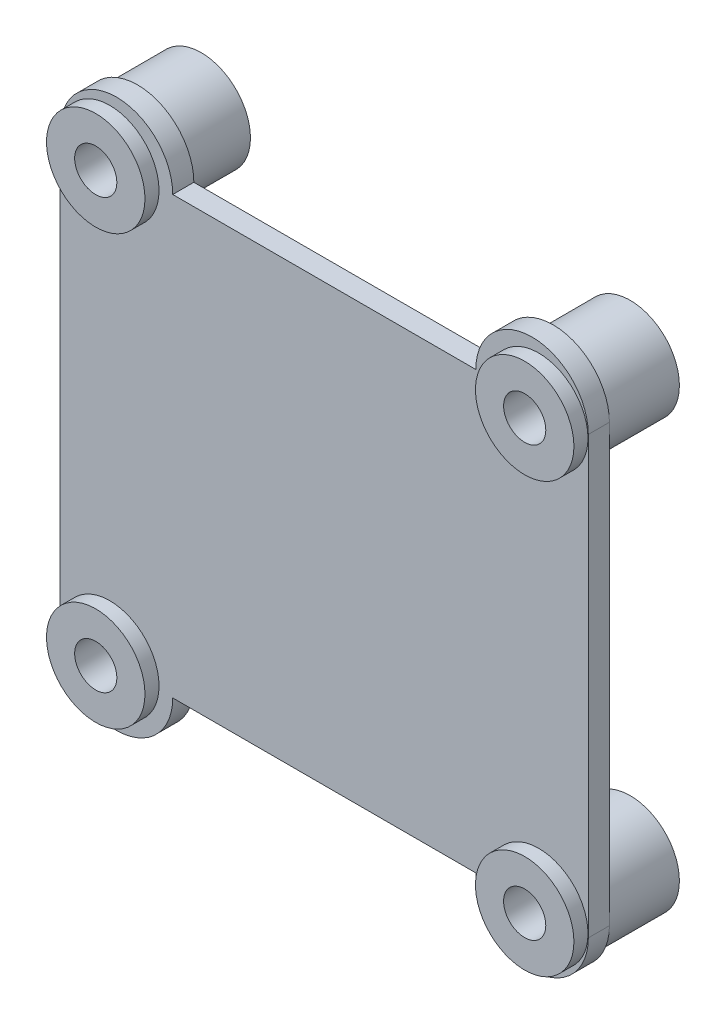
SolidWorks part; units mm, degrees
ref_plane "Alzado" through (0, 0, 0) normal (0, 0, 1) x (1, 0, 0)
ref_plane "Planta" through (0, 0, 0) normal (0, 1, 0) x (1, 0, 0)
ref_plane "Vista lateral" through (0, 0, 0) normal (1, 0, 0) x (0, 0, -1)
sketch "Croquis1" plane through (0, 0, 0) normal (0, 0, 1) x (1, 0, 0)
  line L20 (17.8832, 13.696) -> (17.8832, -17.304)
  line L35 (-19.6668, 13.696) -> (-19.6668, -17.304)
  line L36 (-11.6668, 13.696) -> (9.8832, 13.696)
  line L37 (-19.6668, -1.804) -> (17.8832, -1.804) construction
  line L38 (-11.6668, -17.304) -> (9.8832, -17.304)
  circle A0 centre (-16.1418, 13.446) radius 2.5
  circle A1 centre (14.3582, 13.446) radius 2.5
  circle A2 centre (14.3582, -17.054) radius 2.5
  circle A3 centre (-16.1418, -17.054) radius 2.5
  arc A12 (-11.6668, 13.696) -> (-19.6668, 13.696) centre (-15.6668, 13.696) ccw
  arc A13 (17.8832, 13.696) -> (9.8832, 13.696) centre (13.8832, 13.696) ccw
  arc A14 (17.8832, -17.304) -> (9.8832, -17.304) centre (13.8832, -17.304) cw
  arc A15 (-11.6668, -17.304) -> (-19.6668, -17.304) centre (-15.6668, -17.304) cw
  point P54 (17.8832, 17.696)
  point P57 (-19.6668, 17.696)
  dimension "D3" = 2
  dimension "D1" = 37.55
  dimension "D4" = 2
extrude "Saliente-Extruir1" add sketch "Croquis1" along normal blind 1.5
sketch "Croquis2" plane through (0, 0, 1.5) normal (0, 0, 1) x (1, 0, 0)
  line L1 (-18.6418, -17.054) -> (-13.6418, -17.054)
  circle A1 centre (-16.1418, -17.054) radius 2.5 construction
ref_plane "Plano1" through (0, -17.054, 0) normal (0, -1, 0) x (-1, 0, 0)
sketch "Croquis3" plane through (0, -17.054, 0) normal (0, -1, 0) x (-1, 0, 0)
  line L0 (18.6418, -1.5) -> (19.6418, -1.5)
  line L1 (19.6418, -1.5) -> (19.6418, -2.5)
  line L2 (18.6418, -1.5) -> (13.6418, -1.5) construction
  line L3 (16.1418, -1.5) -> (16.1418, -2.5) construction
  line L5 (16.1418, -2.5) -> (16.1418, 1) construction
  line L7 (19.6418, 5) -> (19.6418, 0)
  line L8 (19.6418, 0) -> (18.6418, 0)
  line L9 (18.6418, 0) -> (18.6418, -1.5)
  line L10 (19.6418, -2.5) -> (17.6418, -2.5)
  line L11 (17.6418, -2.5) -> (17.6418, 5)
  line L12 (17.6418, 5) -> (19.6418, 5)
  dimension "D1" = 5
  dimension "D2" = 1
  dimension "D3" = 1
  dimension "D4" = 1
  dimension "D6" = 2
revolve "Revolución1" add sketch "Croquis3" angle 360 about L5
pattern_linear "MatrizL1" count 2 spacing 30.5 along (1, 0, 0) count 2 spacing 30.5 along (0, 1, 0) of "Revolución1"
